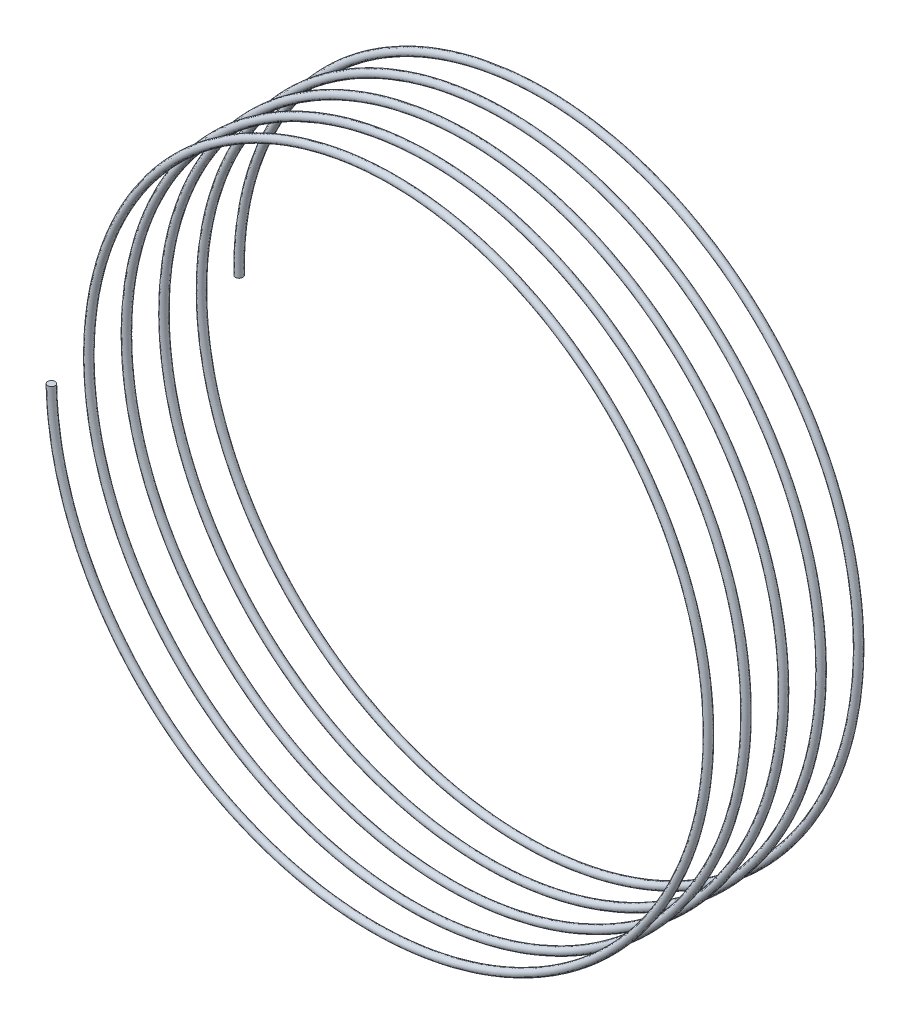
SolidWorks part; units mm, degrees
ref_plane "Plano frontal" through (0, 0, 0) normal (0, 0, 1) x (1, 0, 0)
ref_plane "Plano superior" through (0, 0, 0) normal (0, 1, 0) x (1, 0, 0)
ref_plane "Plano direito" through (0, 0, 0) normal (1, 0, 0) x (0, 0, -1)
sketch "Esboço1" plane through (0, 0, 0) normal (0, 0, 1) x (1, 0, 0)
  circle A0 centre (0, 0) radius 8.5
  dimension "D1" = 17
curve "Hélice/Espiral3" pitch 1 height 5 turns 5
sketch "Esboço6" plane through (0, 0, 0) normal (0, 1, 0) x (1, 0, 0)
  circle A0 centre (-8.5, 0) radius 0.1
  spline S0 degree 3 poles (-8.5, 0) (-8.5, -0.0207) (-8.0574, -0.0626) (-6.1669, -0.125) (-3.3375, -0.1875) (0, -0.25) (3.3375, -0.3125) (6.1669, -0.375) (8.0574, -0.4375) (8.7213, -0.5) (8.0574, -0.5625) (6.1669, -0.625) (3.3375, -0.6875) (0, -0.75) (-3.3375, -0.8125) (-6.1669, -0.875) (-8.0574, -0.9375) (-8.7213, -1) (-8.0574, -1.0625) (-6.1669, -1.125) (-3.3375, -1.1875) (0, -1.25) (3.3375, -1.3125) (6.1669, -1.375) (8.0574, -1.4375) (8.7213, -1.5) (8.0574, -1.5625) (6.1669, -1.625) (3.3375, -1.6875) (0, -1.75) (-3.3375, -1.8125) (-6.1669, -1.875) (-8.0574, -1.9375) (-8.7213, -2) (-8.0574, -2.0625) (-6.1669, -2.125) (-3.3375, -2.1875) (0, -2.25) (3.3375, -2.3125) (6.1669, -2.375) (8.0574, -2.4375) (8.7213, -2.5) (8.0574, -2.5625) (6.1669, -2.625) (3.3375, -2.6875) (0, -2.75) (-3.3375, -2.8125) (-6.1669, -2.875) (-8.0574, -2.9375) (-8.7213, -3) (-8.0574, -3.0625) (-6.1669, -3.125) (-3.3375, -3.1875) (0, -3.25) (3.3375, -3.3125) (6.1669, -3.375) (8.0574, -3.4375) (8.7213, -3.5) (8.0574, -3.5625) (6.1669, -3.625) (3.3375, -3.6875) (0, -3.75) (-3.3375, -3.8125) (-6.1669, -3.875) (-8.0574, -3.9375) (-8.7213, -4) (-8.0574, -4.0625) (-6.1669, -4.125) (-3.3375, -4.1875) (0, -4.25) (3.3375, -4.3125) (6.1669, -4.375) (8.0574, -4.4375) (8.7213, -4.5) (8.0574, -4.5625) (6.1669, -4.625) (3.3375, -4.6875) (0, -4.75) (-3.3375, -4.8125) (-6.1669, -4.875) (-8.0574, -4.9374) (-8.5, -4.9793) (-8.5, -5) knots 0 0 0 0 0.0125 0.025 0.0375 0.05 0.0625 0.075 0.0875 0.1 0.1125 0.125 0.1375 0.15 0.1625 0.175 0.1875 0.2 0.2125 0.225 0.2375 0.25 0.2625 0.275 0.2875 0.3 0.3125 0.325 0.3375 0.35 0.3625 0.375 0.3875 0.4 0.4125 0.425 0.4375 0.45 0.4625 0.475 0.4875 0.5 0.5125 0.525 0.5375 0.55 0.5625 0.575 0.5875 0.6 0.6125 0.625 0.6375 0.65 0.6625 0.675 0.6875 0.7 0.7125 0.725 0.7375 0.75 0.7625 0.775 0.7875 0.8 0.8125 0.825 0.8375 0.85 0.8625 0.875 0.8875 0.9 0.9125 0.925 0.9375 0.95 0.9625 0.975 0.9875 1 1 1 1 construction
  point P2 (0, 0)
sweep "Varredura1" add profiles "Esboço6" path "Hélice/Espiral3"
